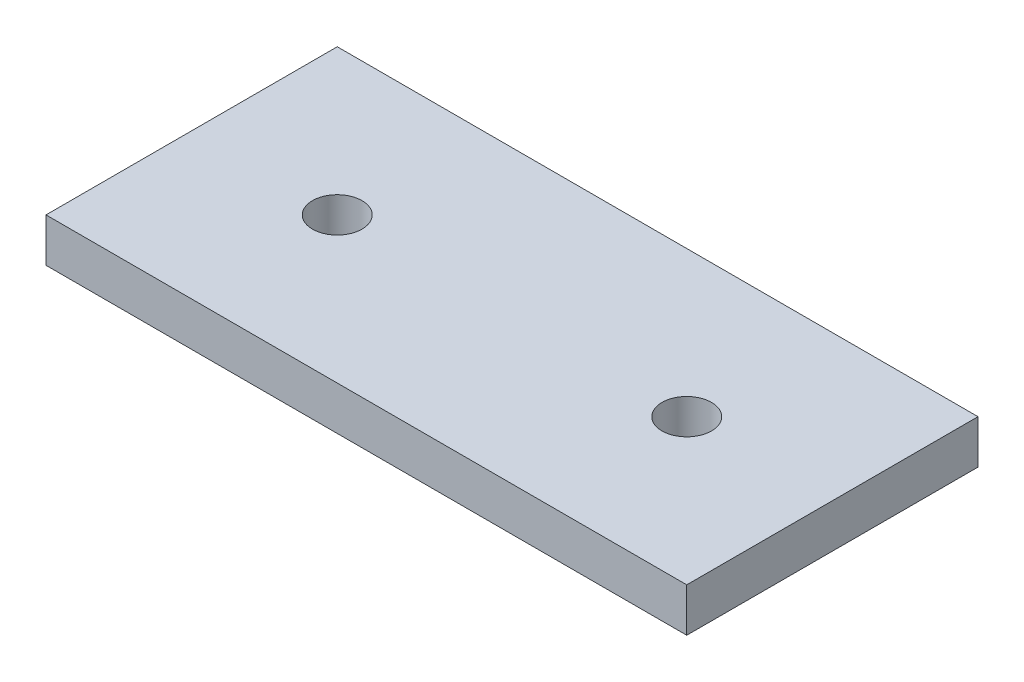
SolidWorks part; units mm, degrees
ref_plane "Front Plane" through (0, 0, 0) normal (0, 0, 1) x (1, 0, 0)
ref_plane "Top Plane" through (0, 0, 0) normal (0, 1, 0) x (1, 0, 0)
ref_plane "Right Plane" through (0, 0, 0) normal (1, 0, 0) x (0, 0, -1)
sketch "Sketch1" plane through (0, 0, 0) normal (0, 1, 0) x (1, 0, 0)
  line L1 (-22, -10) -> (22, -10)
  line L2 (-22, -10) -> (-22, 10)
  line L3 (-22, 10) -> (22, 10)
  line L4 (22, -10) -> (22, 10)
extrude "Joiner Plate" add sketch "Sketch1" along normal blind 3
sketch "Sketch2" plane through (0, 0, 0) normal (0, 1, 0) x (1, 0, 0)
  circle A0 centre (-12, 0) radius 1.7
  circle A1 centre (12, 0) radius 1.7
extrude "Bolt Holes" cut sketch "Sketch2" against normal through all and the other way through all
